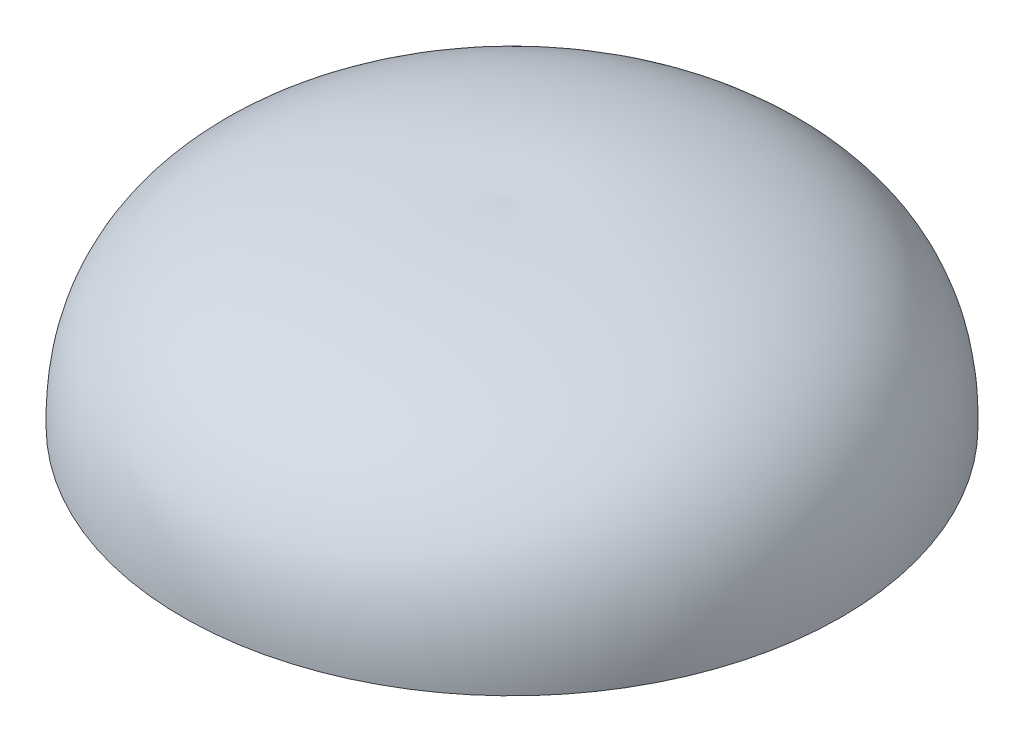
SolidWorks part; units mm, degrees
material "PC High Viscosity"
ref_plane "Front Plane" through (0, 0, 0) normal (0, 0, 1) x (1, 0, 0)
ref_plane "Top Plane" through (0, 0, 0) normal (0, 1, 0) x (1, 0, 0)
ref_plane "Right Plane" through (0, 0, 0) normal (1, 0, 0) x (0, 0, -1)
sketch "Sketch2" plane through (0, 0, 0) normal (0, 0, 1) x (1, 0, 0)
  line L1 (0, 0) -> (0, 15)
  line L2 (0, 0) -> (25, 0)
  spline S0 degree 3 poles (0, 15) (4.1872, 15.2787) (14.9664, 14.5895) (25.2543, 9.139) (25, 0) knots 0 0 0 0 0.386239 1 1 1 1
revolve "Revolve1" add sketch "Sketch2" angle 360 about L1
